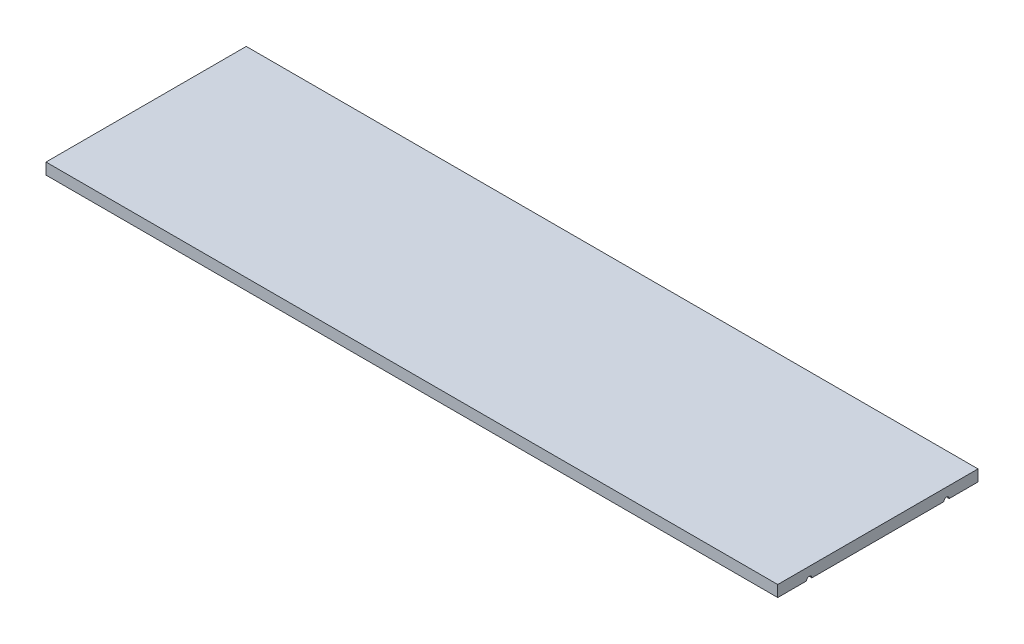
SolidWorks part; units mm, degrees
ref_plane "Front Plane" through (0, 0, 0) normal (0, 0, 1) x (1, 0, 0)
ref_plane "Top Plane" through (0, 0, 0) normal (0, 1, 0) x (1, 0, 0)
ref_plane "Right Plane" through (0, 0, 0) normal (1, 0, 0) x (0, 0, -1)
ref_plane "Back Plane" through (0, 0, -318) normal (0, 0, 1) x (1, 0, 0)
ref_plane "Bottom Plane" through (0, -18, 0) normal (0, 1, 0) x (-1, 0, 0)
ref_plane "Left Plane" through (-1162, 0, 0) normal (1, 0, 0) x (0, 0, -1)
sketch "Sketch1" plane through (0, -18, 0) normal (0, 1, 0) x (-1, 0, 0)
  line L0 (1162, 55) -> (1162, -55) construction
  line L1 (1162, -318) -> (0, -318)
  line L2 (1162, -318) -> (1162, 0)
  line L3 (1162, 0) -> (0, 0)
  line L4 (0, -318) -> (0, 0)
  line L5 (55, -318) -> (-55, -318) construction
  line L7 (0, 55) -> (0, -55) construction
  line L8 (55, 0) -> (-55, 0) construction
extrude "Adj Shelf" add sketch "Sketch1" along normal up to surface (18 mm away) up to plane "Top Plane"
sketch "Sketch2" plane through (-1162, 0, 0) normal (1, 0, 0) x (0, 0, -1)
  line L0 (318, -18) -> (0, -18) construction
  circle A0 centre (50, -18) radius 4.25
  circle A1 centre (268, -18) radius 4.25
  dimension "D1" = 8.5
  dimension "D2" = 50
  dimension "D3" = 50
extrude "Extrude3" cut sketch "Sketch2" along normal blind 18
sketch "Sketch4" plane through (0, 0, 0) normal (1, 0, 0) x (0, 0, -1)
  line L1 (45.75, -18) -> (54.25, -18)
  line L2 (263.75, -18) -> (272.25, -18)
  arc A0 (272.25, -18) -> (263.75, -18) centre (268, -18) ccw construction
  arc A1 (54.25, -18) -> (45.75, -18) centre (50, -18) ccw construction
  arc A2 (272.25, -18) -> (263.75, -18) centre (268, -18) ccw
  arc A3 (54.25, -18) -> (45.75, -18) centre (50, -18) ccw
extrude "Extrude4" cut sketch "Sketch4" against normal blind 18
